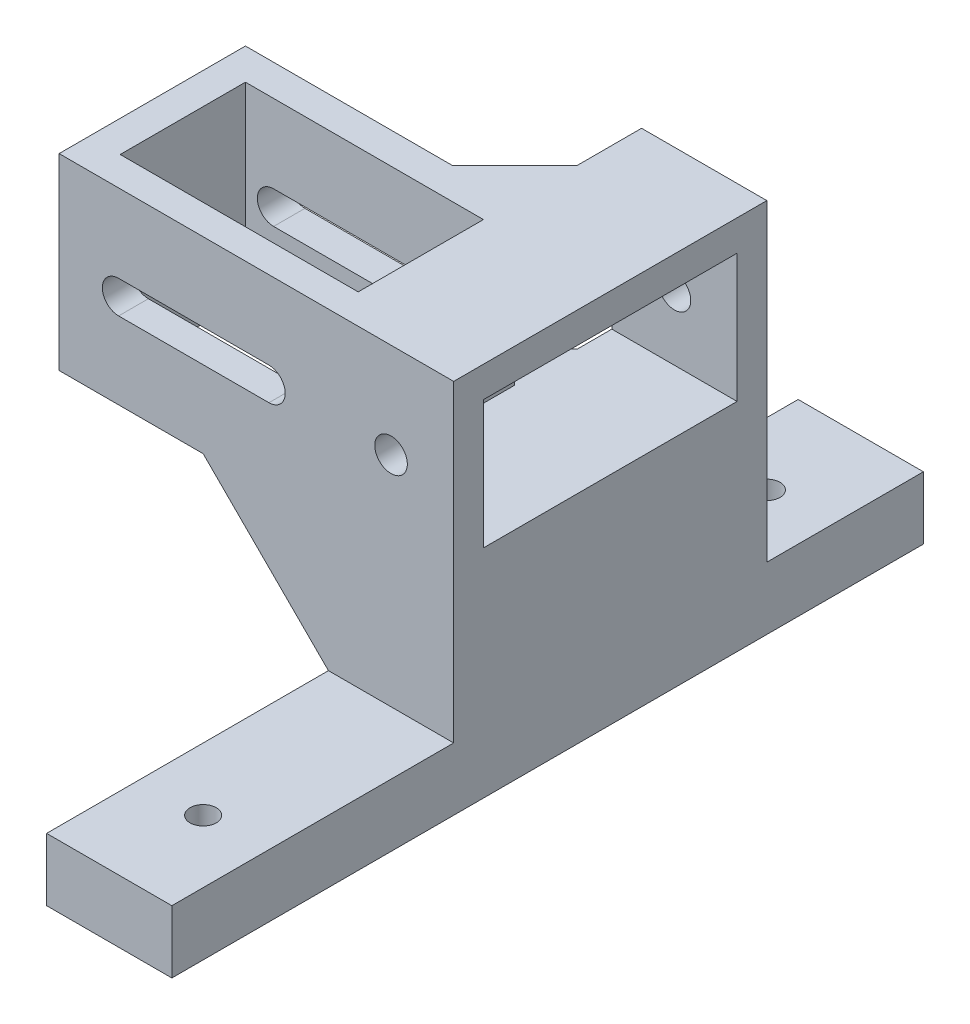
SolidWorks part; units mm, degrees
ref_plane "Front Plane" through (0, 0, 0) normal (0, 0, 1) x (1, 0, 0)
ref_plane "Top Plane" through (0, 0, 0) normal (0, 1, 0) x (1, 0, 0)
ref_plane "Right Plane" through (0, 0, 0) normal (1, 0, 0) x (0, 0, -1)
sketch "Sketch4" plane through (0, 0, 0) normal (0, 1, 0) x (1, 0, 0)
  line L1 (0, 0) -> (20, 0)
  line L2 (0, 0) -> (0, 120)
  line L3 (0, 120) -> (20, 120)
  line L4 (20, 0) -> (20, 120)
  dimension "D1" = 120
  dimension "D2" = 20
extrude "Boss-Extrude4" add sketch "Sketch4" along normal blind 10
sketch "Sketch5" plane through (0, 10, 0) normal (0, 1, 0) x (1, 0, 0)
  line L0 (10, 0) -> (10, 15) construction
  line L1 (0, 0) -> (20, 0) construction
  line L2 (10, 15) -> (10, 105) construction
  circle A0 centre (10, 105) radius 2.1
  circle A1 centre (10, 15) radius 2.1
  dimension "D3" = 4.2
  dimension "D4" = 4.2
  dimension "D1" = 15
  dimension "D2" = 90
extrude "Cut-Extrude1" cut sketch "Sketch5" against normal up to surface (10 mm away) up to face at (10, 0, -60)
sketch "Sketch6" plane through (0, 10, 0) normal (0, 1, 0) x (1, 0, 0)
  line L1 (0, 95) -> (20, 95)
  line L2 (0, 95) -> (0, 45)
  line L3 (0, 45) -> (20, 45)
  line L4 (20, 95) -> (20, 45)
  line L6 (0, 120) -> (0, 0) construction
  line L7 (20, 0) -> (20, 120) construction
  line L8 (20, 120) -> (0, 120) construction
  dimension "D1" = 50
  dimension "D2" = 20
  dimension "D3" = 25
extrude "Boss-Extrude5" add sketch "Sketch6" along normal blind 50
sketch "Sketch7" plane through (0, 0, 0) normal (-1, 0, 0) x (0, 0, 1)
  line L1 (-49.75, 34.6) -> (-90.25, 34.6)
  line L2 (-49.75, 34.6) -> (-49.75, 55.1)
  line L3 (-49.75, 55.1) -> (-90.25, 55.1)
  line L4 (-90.25, 34.6) -> (-90.25, 55.1)
  line L7 (-95, 60) -> (-45, 60) construction
  point P4 (-70, 60)
  point P5 (-70, 55.1)
  point P8 (0, 0)
  dimension "D1" = 20.5
  dimension "D2" = 40.5
extrude "Cut-Extrude2" cut sketch "Sketch7" against normal up to surface (20 mm away) up to face at (20, 20, -65)
sketch "Sketch8" plane through (0, 0, -90.25) normal (0, 0, 1) x (1, 0, 0)
  line L0 (0, 44.85) -> (20, 44.85) construction
  line L1 (0, 55.1) -> (0, 34.6) construction
  line L2 (20, 34.6) -> (20, 55.1) construction
  circle A0 centre (10, 44.85) radius 2.6
  dimension "D1" = 5.2
extrude "Cut-Extrude3" cut sketch "Sketch8" against normal mid plane 100
sketch "Sketch9" plane through (0, 0, 0) normal (-1, 0, 0) x (0, 0, 1)
  line L0 (-49.75, 60) -> (-49.75, 30)
  line L5 (-49.75, 30) -> (-45, 30)
  line L6 (-95, 60) -> (-45, 60) construction
  line L7 (-74.75, 60) -> (-69.75, 60)
  line L19 (-45, 30) -> (-45, 60)
  line L20 (-45, 60) -> (-49.75, 60)
  line L24 (-74.75, 60) -> (-74.75, 30)
  line L25 (-74.75, 30) -> (-69.75, 30)
  line L26 (-69.75, 60) -> (-69.75, 30)
  point P16 (0, 0)
  point P17 (0, 0)
  dimension "D2" = 30
  dimension "D3" = 30
  dimension "D4" = 5
  dimension "D5" = 20
extrude "Boss-Extrude6" add sketch "Sketch9" along normal blind 40
sketch "Sketch10" plane through (0, 0, -74.75) normal (0, 0, -1) x (-1, 0, 0)
  line L0 (33.5, 44.9) -> (9.5, 44.9) construction
  line L1 (33.5, 42.3) -> (9.5, 42.3)
  line L2 (33.5, 47.5) -> (9.5, 47.5)
  line L3 (40, 60) -> (40, 30) construction
  line L4 (40, 60) -> (0, 60) construction
  arc A0 (33.5, 42.3) -> (33.5, 47.5) centre (33.5, 44.9) ccw
  arc A1 (9.5, 47.5) -> (9.5, 42.3) centre (9.5, 44.9) ccw
  point P2 (21.5, 44.9)
  dimension "D1" = 5.2
  dimension "D2" = 6.5
  dimension "D3" = 24
  dimension "D4" = 15.1
extrude "Cut-Extrude4" cut sketch "Sketch10" against normal blind 40
sketch "Sketch11" plane through (0, 0, -74.75) normal (0, 0, -1) x (-1, 0, 0)
  line L0 (40, 60) -> (0, 60) construction
  line L1 (38, 60) -> (43, 60)
  line L2 (38, 60) -> (38, 30)
  line L3 (38, 30) -> (43, 30)
  line L4 (43, 60) -> (43, 30)
  line L5 (40, 60) -> (40, 30) construction
  dimension "D1" = 30
  dimension "D2" = 5
  dimension "D3" = 2
extrude "Boss-Extrude7" add sketch "Sketch11" against normal up to surface (29.75 mm away)
sketch "Sketch12" plane through (-43, 0, 0) normal (-1, 0, 0) x (0, 0, 1)
  line L0 (-59.875, 60) -> (-59.875, 30) construction
  line L1 (-45, 60) -> (-74.75, 60) construction
  line L2 (-45, 30) -> (-74.75, 30) construction
  circle A0 centre (-59.875, 45) radius 2.1
  dimension "D1" = 4.2
extrude "Cut-Extrude5" cut sketch "Sketch12" against normal blind 5
chamfer "Chamfer1" distance 20 angle 45 2 edges at (0, 30, -47.375) (0, 30, -72.25)
chamfer "Chamfer2" distance 10 angle 45 2 edges at (0, 57.55, -74.75) (0, 22.3, -74.75)
